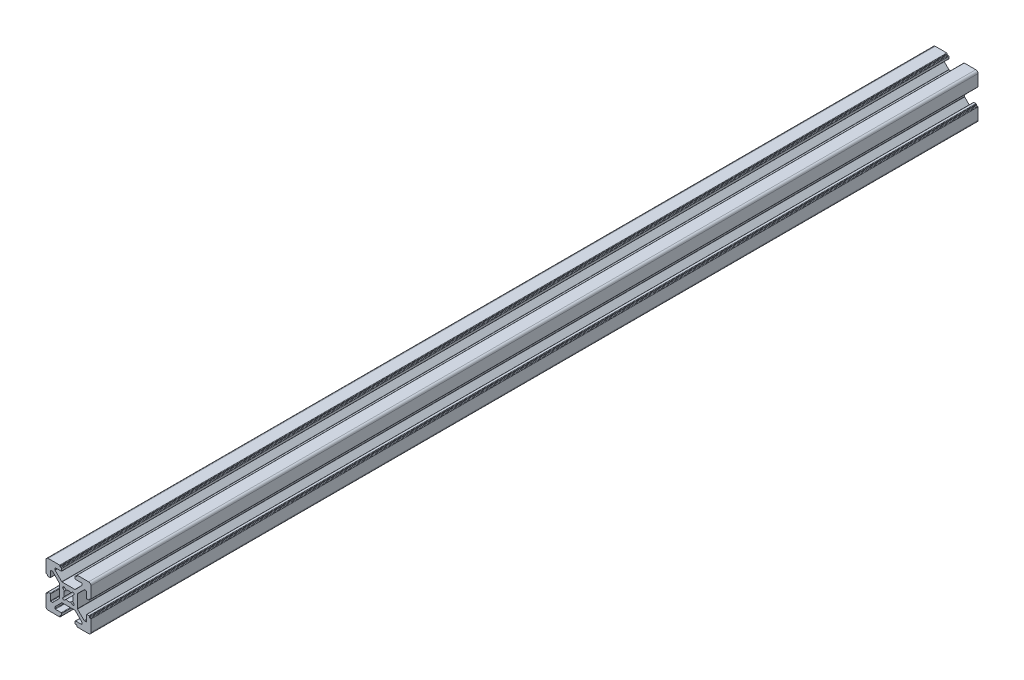
SolidWorks part; units mm, degrees
ref_plane "Plano frontal" through (0, 0, 0) normal (0, 0, 1) x (1, 0, 0)
ref_plane "Plano superior" through (0, 0, 0) normal (0, 1, 0) x (1, 0, 0)
ref_plane "Plano direito" through (0, 0, 0) normal (1, 0, 0) x (0, 0, -1)
sketch "Model" plane through (0, 0, 0) normal (0, 0, 1) x (1, 0, 0)
  line L0 (-2.4, -1.6679) -> (-1.8051, -1.0731)
  line L1 (-1.8051, 1.0731) -> (-2.4, 1.6679)
  line L2 (-1.6679, 2.4) -> (-1.0731, 1.8051)
  line L3 (1.0731, 1.8051) -> (1.6679, 2.4)
  line L4 (2.4, 1.6679) -> (1.8051, 1.0731)
  line L5 (1.8051, -1.0731) -> (2.4, -1.6679)
  line L6 (1.6679, -2.4) -> (1.0731, -1.8051)
  line L7 (-1.0731, -1.8051) -> (-1.6679, -2.4)
  line L8 (-10, 9) -> (-10, 3.9)
  line L9 (-9.8, 3.7) -> (-9.5, 3.7)
  line L10 (-9.3, 3.5) -> (-9.3, 3.2)
  line L11 (-9.1, 3) -> (-8.2, 3)
  line L12 (-8, 3.2) -> (-8, 5.8)
  line L13 (-7.8, 6) -> (-7.1435, 6)
  line L14 (-4.0586, 2.9979) -> (-7.0021, 5.9414)
  line L15 (-2.9979, 4.0586) -> (-5.9414, 7.0021)
  line L16 (-6, 7.8) -> (-6, 7.1435)
  line L17 (-3.2, 8) -> (-5.8, 8)
  line L18 (-3, 9.1) -> (-3, 8.2)
  line L19 (-3.5, 9.3) -> (-3.2, 9.3)
  line L20 (-3.7, 9.8) -> (-3.7, 9.5)
  line L21 (-9, 10) -> (-3.9, 10)
  line L22 (10, 9) -> (10, 3.9)
  line L23 (9.8, 3.7) -> (9.5, 3.7)
  line L24 (9.3, 3.5) -> (9.3, 3.2)
  line L25 (9.1, 3) -> (8.2, 3)
  line L26 (8, 3.2) -> (8, 5.8)
  line L27 (7.8, 6) -> (7.1435, 6)
  line L28 (7.0021, 5.9414) -> (4.0586, 2.9979)
  line L29 (-2.8565, 4) -> (2.8565, 4)
  line L30 (2.9979, 4.0586) -> (5.9414, 7.0021)
  line L31 (6, 7.1435) -> (6, 7.8)
  line L32 (5.8, 8) -> (3.2, 8)
  line L33 (3, 8.2) -> (3, 9.1)
  line L34 (3.2, 9.3) -> (3.5, 9.3)
  line L35 (3.7, 9.5) -> (3.7, 9.8)
  line L36 (3.9, 10) -> (9, 10)
  line L37 (10, -9) -> (10, -3.9)
  line L38 (9.8, -3.7) -> (9.5, -3.7)
  line L39 (9.3, -3.5) -> (9.3, -3.2)
  line L40 (9.1, -3) -> (8.2, -3)
  line L41 (8, -3.2) -> (8, -5.8)
  line L42 (7.8, -6) -> (7.1435, -6)
  line L43 (4.0586, -2.9979) -> (7.0021, -5.9414)
  line L44 (4, -2.8565) -> (4, 2.8565)
  line L45 (2.9979, -4.0586) -> (5.9414, -7.0021)
  line L46 (6, -7.8) -> (6, -7.1435)
  line L47 (3.2, -8) -> (5.8, -8)
  line L48 (3, -9.1) -> (3, -8.2)
  line L49 (3.5, -9.3) -> (3.2, -9.3)
  line L50 (3.7, -9.8) -> (3.7, -9.5)
  line L51 (9, -10) -> (3.9, -10)
  line L52 (-10, -9) -> (-10, -3.9)
  line L53 (-9.8, -3.7) -> (-9.5, -3.7)
  line L54 (-9.3, -3.5) -> (-9.3, -3.2)
  line L55 (-9.1, -3) -> (-8.2, -3)
  line L56 (-8, -3.2) -> (-8, -5.8)
  line L57 (-7.8, -6) -> (-7.1435, -6)
  line L58 (-7.0021, -5.9414) -> (-4.0586, -2.9979)
  line L59 (-4, -2.8565) -> (-4, 2.8565)
  line L60 (2.8565, -4) -> (-2.8565, -4)
  line L61 (-2.9979, -4.0586) -> (-5.9414, -7.0021)
  line L62 (-6, -7.1435) -> (-6, -7.8)
  line L63 (-5.8, -8) -> (-3.2, -8)
  line L64 (-3, -8.2) -> (-3, -9.1)
  line L65 (-3.2, -9.3) -> (-3.5, -9.3)
  line L66 (-3.7, -9.5) -> (-3.7, -9.8)
  line L67 (-3.9, -10) -> (-9, -10)
  arc A0 (1.6679, -2.4) -> (2.5516, -2.034) centre (2.034, -2.034) ccw
  arc A1 (1.8051, -1.0731) -> (2.1, 0) centre (0, 0) ccw
  arc A2 (2.4, 1.6679) -> (2.5516, 2.034) centre (2.034, 2.034) ccw
  arc A3 (-2.5516, 2.034) -> (-2.4, 1.6679) centre (-2.034, 2.034) ccw
  arc A4 (-2.1, 0) -> (-1.8051, -1.0731) centre (0, 0) ccw
  arc A5 (-2.5516, -2.034) -> (-1.6679, -2.4) centre (-2.034, -2.034) ccw
  arc A6 (-2.4, -1.6679) -> (-2.5516, -2.034) centre (-2.034, -2.034) ccw
  arc A7 (-1.8051, 1.0731) -> (-2.1, 0) centre (0, 0) ccw
  arc A8 (-1.6679, 2.4) -> (-2.5516, 2.034) centre (-2.034, 2.034) ccw
  arc A9 (1.0731, 1.8051) -> (-1.0731, 1.8051) centre (0, 0) ccw
  arc A10 (2.5516, 2.034) -> (1.6679, 2.4) centre (2.034, 2.034) ccw
  arc A11 (2.1, 0) -> (1.8051, 1.0731) centre (0, 0) ccw
  arc A12 (2.5516, -2.034) -> (2.4, -1.6679) centre (2.034, -2.034) ccw
  arc A13 (-1.0731, -1.8051) -> (1.0731, -1.8051) centre (0, 0) ccw
  arc A14 (-9, 10) -> (-10, 9) centre (-9, 9) ccw
  arc A15 (-10, 3.9) -> (-9.8, 3.7) centre (-9.8, 3.9) ccw
  arc A16 (-9.3, 3.5) -> (-9.5, 3.7) centre (-9.5, 3.5) ccw
  arc A17 (-9.3, 3.2) -> (-9.1, 3) centre (-9.1, 3.2) ccw
  arc A18 (-8.2, 3) -> (-8, 3.2) centre (-8.2, 3.2) ccw
  arc A19 (-7.8, 6) -> (-8, 5.8) centre (-7.8, 5.8) ccw
  arc A20 (-7.0021, 5.9414) -> (-7.1435, 6) centre (-7.1435, 5.8) ccw
  arc A21 (-4, 2.8565) -> (-4.0586, 2.9979) centre (-4.2, 2.8565) ccw
  arc A22 (-2.9979, 4.0586) -> (-2.8565, 4) centre (-2.8565, 4.2) ccw
  arc A23 (-6, 7.1435) -> (-5.9414, 7.0021) centre (-5.8, 7.1435) ccw
  arc A24 (-5.8, 8) -> (-6, 7.8) centre (-5.8, 7.8) ccw
  arc A25 (-3.2, 8) -> (-3, 8.2) centre (-3.2, 8.2) ccw
  arc A26 (-3, 9.1) -> (-3.2, 9.3) centre (-3.2, 9.1) ccw
  arc A27 (-3.7, 9.5) -> (-3.5, 9.3) centre (-3.5, 9.5) ccw
  arc A28 (-3.7, 9.8) -> (-3.9, 10) centre (-3.9, 9.8) ccw
  arc A29 (10, 9) -> (9, 10) centre (9, 9) ccw
  arc A30 (9.8, 3.7) -> (10, 3.9) centre (9.8, 3.9) ccw
  arc A31 (9.5, 3.7) -> (9.3, 3.5) centre (9.5, 3.5) ccw
  arc A32 (9.1, 3) -> (9.3, 3.2) centre (9.1, 3.2) ccw
  arc A33 (8, 3.2) -> (8.2, 3) centre (8.2, 3.2) ccw
  arc A34 (8, 5.8) -> (7.8, 6) centre (7.8, 5.8) ccw
  arc A35 (7.1435, 6) -> (7.0021, 5.9414) centre (7.1435, 5.8) ccw
  arc A36 (4.0586, 2.9979) -> (4, 2.8565) centre (4.2, 2.8565) ccw
  arc A37 (2.8565, 4) -> (2.9979, 4.0586) centre (2.8565, 4.2) ccw
  arc A38 (5.9414, 7.0021) -> (6, 7.1435) centre (5.8, 7.1435) ccw
  arc A39 (6, 7.8) -> (5.8, 8) centre (5.8, 7.8) ccw
  arc A40 (3, 8.2) -> (3.2, 8) centre (3.2, 8.2) ccw
  arc A41 (3.2, 9.3) -> (3, 9.1) centre (3.2, 9.1) ccw
  arc A42 (3.5, 9.3) -> (3.7, 9.5) centre (3.5, 9.5) ccw
  arc A43 (3.9, 10) -> (3.7, 9.8) centre (3.9, 9.8) ccw
  arc A44 (9, -10) -> (10, -9) centre (9, -9) ccw
  arc A45 (10, -3.9) -> (9.8, -3.7) centre (9.8, -3.9) ccw
  arc A46 (9.3, -3.5) -> (9.5, -3.7) centre (9.5, -3.5) ccw
  arc A47 (9.3, -3.2) -> (9.1, -3) centre (9.1, -3.2) ccw
  arc A48 (8.2, -3) -> (8, -3.2) centre (8.2, -3.2) ccw
  arc A49 (7.8, -6) -> (8, -5.8) centre (7.8, -5.8) ccw
  arc A50 (7.0021, -5.9414) -> (7.1435, -6) centre (7.1435, -5.8) ccw
  arc A51 (4, -2.8565) -> (4.0586, -2.9979) centre (4.2, -2.8565) ccw
  arc A52 (2.9979, -4.0586) -> (2.8565, -4) centre (2.8565, -4.2) ccw
  arc A53 (6, -7.1435) -> (5.9414, -7.0021) centre (5.8, -7.1435) ccw
  arc A54 (5.8, -8) -> (6, -7.8) centre (5.8, -7.8) ccw
  arc A55 (3.2, -8) -> (3, -8.2) centre (3.2, -8.2) ccw
  arc A56 (3, -9.1) -> (3.2, -9.3) centre (3.2, -9.1) ccw
  arc A57 (3.7, -9.5) -> (3.5, -9.3) centre (3.5, -9.5) ccw
  arc A58 (3.7, -9.8) -> (3.9, -10) centre (3.9, -9.8) ccw
  arc A59 (-10, -9) -> (-9, -10) centre (-9, -9) ccw
  arc A60 (-9.8, -3.7) -> (-10, -3.9) centre (-9.8, -3.9) ccw
  arc A61 (-9.5, -3.7) -> (-9.3, -3.5) centre (-9.5, -3.5) ccw
  arc A62 (-9.1, -3) -> (-9.3, -3.2) centre (-9.1, -3.2) ccw
  arc A63 (-8, -3.2) -> (-8.2, -3) centre (-8.2, -3.2) ccw
  arc A64 (-8, -5.8) -> (-7.8, -6) centre (-7.8, -5.8) ccw
  arc A65 (-7.1435, -6) -> (-7.0021, -5.9414) centre (-7.1435, -5.8) ccw
  arc A66 (-4.0586, -2.9979) -> (-4, -2.8565) centre (-4.2, -2.8565) ccw
  arc A67 (-2.8565, -4) -> (-2.9979, -4.0586) centre (-2.8565, -4.2) ccw
  arc A68 (-5.9414, -7.0021) -> (-6, -7.1435) centre (-5.8, -7.1435) ccw
  arc A69 (-6, -7.8) -> (-5.8, -8) centre (-5.8, -7.8) ccw
  arc A70 (-3, -8.2) -> (-3.2, -8) centre (-3.2, -8.2) ccw
  arc A71 (-3.2, -9.3) -> (-3, -9.1) centre (-3.2, -9.1) ccw
  arc A72 (-3.5, -9.3) -> (-3.7, -9.5) centre (-3.5, -9.5) ccw
  arc A73 (-3.9, -10) -> (-3.7, -9.8) centre (-3.9, -9.8) ccw
extrude "Ressalto-extrusão1" add sketch "Model" along normal mid plane 395 contours A9 L2 A8 A3 L1 A7 A4 L0 A6 A5 L7 A13 L6 A0 A12 L5 A1 A11 L4 A2 A10 L3
